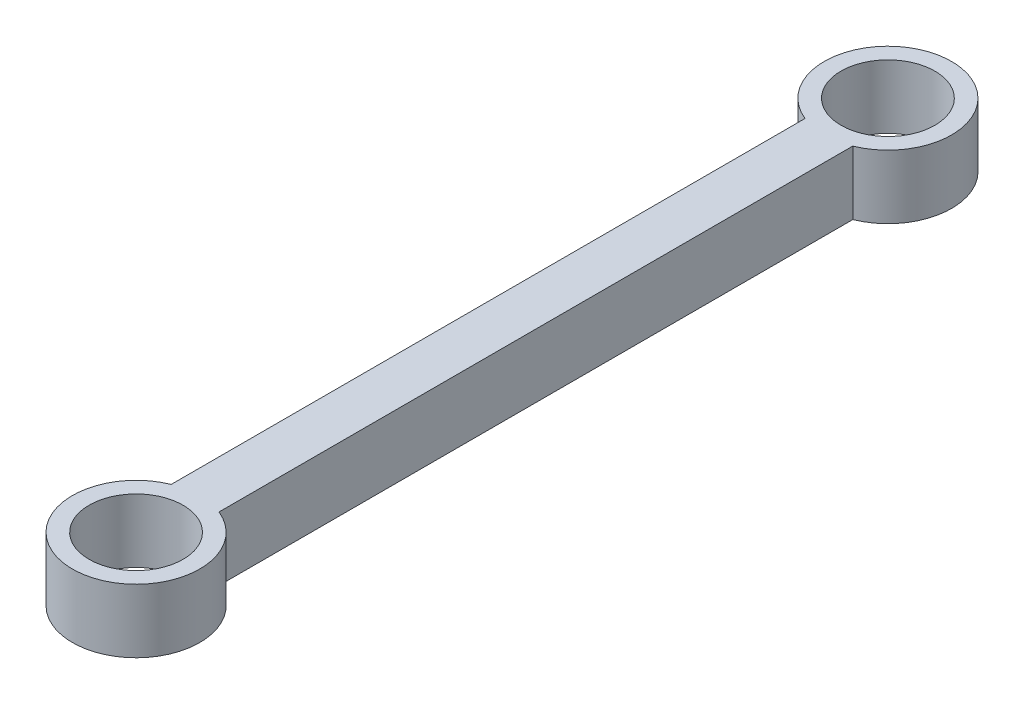
SolidWorks part; units mm, degrees
ref_plane "Front Plane" through (0, 0, 0) normal (0, 0, 1) x (1, 0, 0)
ref_plane "Top Plane" through (0, 0, 0) normal (0, 1, 0) x (1, 0, 0)
ref_plane "Right Plane" through (0, 0, 0) normal (1, 0, 0) x (0, 0, -1)
sketch "Sketch1" plane through (0, 0, 0) normal (0, 1, 0) x (1, 0, 0)
  line L0 (0, 0) -> (0, 47.22) construction
  line L1 (-1.5, 43.5119) -> (-1.5, 3.7081)
  line L2 (1.5, 43.5119) -> (1.5, 3.7081)
  circle A0 centre (0, 47.22) radius 2.95
  circle A1 centre (0, 0) radius 2.95
  arc A2 (1.5, 43.5119) -> (-1.5, 43.5119) centre (0, 47.22) ccw
  arc A3 (-1.5, 3.7081) -> (1.5, 3.7081) centre (0, 0) ccw
  dimension "D2" = 5.9
  dimension "D3" = 5.9
  dimension "D4" = 8
  dimension "D5" = 8
  dimension "D1" = 47.22
  dimension "D6" = 1.5
  dimension "D7" = 1.5
extrude "Boss-Extrude1" add sketch "Sketch1" along normal blind 4
